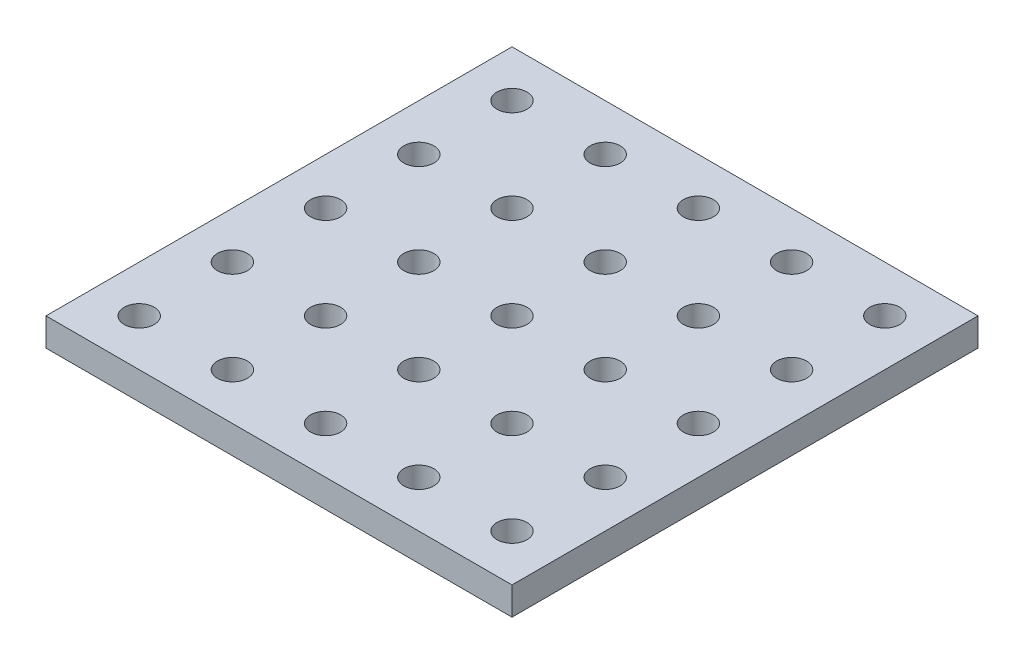
SolidWorks part; units mm, degrees
ref_plane "Front Plane" through (0, 0, 0) normal (0, 0, 1) x (1, 0, 0)
ref_plane "Top Plane" through (0, 0, 0) normal (0, 1, 0) x (1, 0, 0)
ref_plane "Right Plane" through (0, 0, 0) normal (1, 0, 0) x (0, 0, -1)
sketch "Sketch1" plane through (0, 0, 0) normal (0, 1, 0) x (1, 0, 0)
  line L1 (-125, 125) -> (125, 125)
  line L2 (-125, 125) -> (-125, -125)
  line L3 (-125, -125) -> (125, -125)
  line L4 (125, 125) -> (125, -125)
  point P4 (0, 125)
  point P6 (-125, 0)
  dimension "D1" = 250
extrude "Boss-Extrude1" add sketch "Sketch1" along normal blind 15
sketch "Sketch2" plane through (0, 15, 0) normal (0, 1, 0) x (1, 0, 0)
  line L0 (125, 125) -> (-125, 125) construction
  line L2 (-100, 125) -> (-100, 100) construction
  line L3 (-100, 100) -> (-125, 100) construction
  line L4 (-125, 125) -> (-125, -125) construction
  circle A0 centre (-100, 100) radius 8.05
  circle A1 centre (-50, 100) radius 8.05
  circle A2 centre (0, 100) radius 8.05
  circle A3 centre (50, 100) radius 8.05
  circle A4 centre (100, 100) radius 8.05
  circle A5 centre (-50, 50) radius 8.05
  circle A6 centre (0, 50) radius 8.05
  circle A7 centre (50, 50) radius 8.05
  circle A8 centre (100, 50) radius 8.05
  circle A9 centre (-50, 0) radius 8.05
  circle A10 centre (0, 0) radius 8.05
  circle A11 centre (50, 0) radius 8.05
  circle A12 centre (100, 0) radius 8.05
  circle A13 centre (-50, -50) radius 8.05
  circle A14 centre (0, -50) radius 8.05
  circle A15 centre (50, -50) radius 8.05
  circle A16 centre (100, -50) radius 8.05
  circle A17 centre (-50, -100) radius 8.05
  circle A18 centre (0, -100) radius 8.05
  circle A19 centre (50, -100) radius 8.05
  circle A20 centre (100, -100) radius 8.05
  circle A21 centre (-100, 50) radius 8.05
  circle A22 centre (-100, 0) radius 8.05
  circle A23 centre (-100, -50) radius 8.05
  circle A24 centre (-100, -100) radius 8.05
  dimension "D1" = 16.1
  dimension "D4" = 25
  dimension "D2" = 5
  dimension "D3" = 5
extrude "Cut-Extrude1" cut sketch "Sketch2" against normal through all
